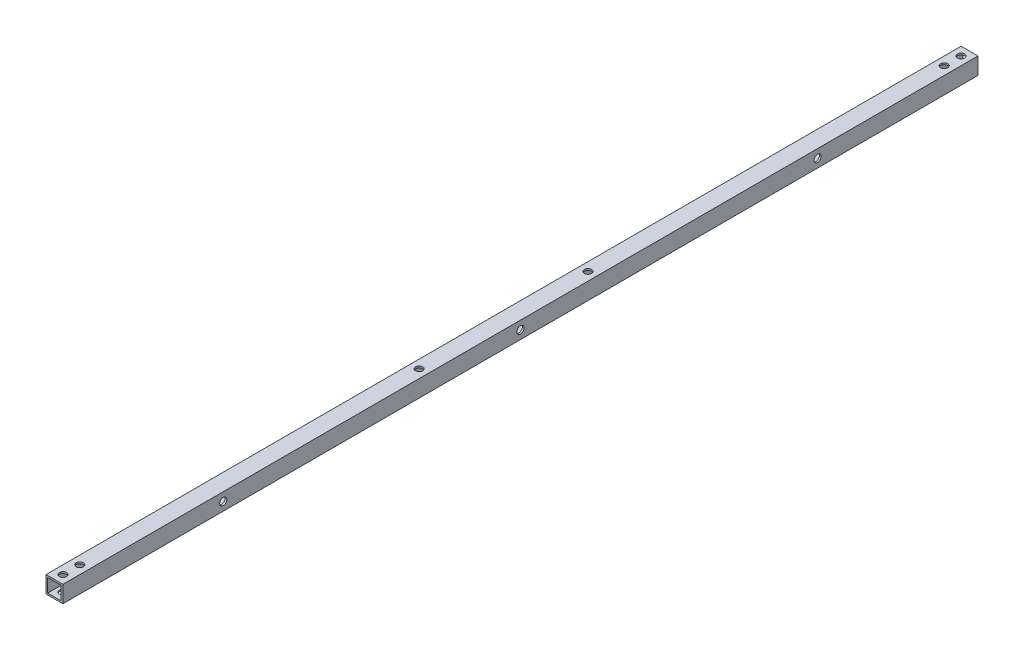
SolidWorks part; units mm, degrees
ref_plane "Front Plane" through (0, 0, 0) normal (0, 0, 1) x (1, 0, 0)
ref_plane "Top Plane" through (0, 0, 0) normal (0, 1, 0) x (1, 0, 0)
ref_plane "Right Plane" through (0, 0, 0) normal (1, 0, 0) x (0, 0, -1)
sketch "Sketch1" plane through (0, 0, 0) normal (0, 0, 1) x (1, 0, 0)
  line L1 (0, 0) -> (10, 0)
  line L2 (0, 0) -> (0, 10)
  line L3 (0, 10) -> (10, 10)
  line L4 (10, 0) -> (10, 10)
  line L5 (1, 9) -> (9, 9)
  line L6 (1, 9) -> (1, 1)
  line L7 (1, 1) -> (9, 1)
  line L8 (9, 9) -> (9, 1)
  dimension "D1" = 10
  dimension "D2" = 10
  dimension "D3" = 8
  dimension "D4" = 8
  dimension "D5" = 1
  dimension "D6" = 1
extrude "Boss-Extrude1" add sketch "Sketch1" along normal blind 542
sketch "Sketch2" plane through (0, 10, 0) normal (0, 1, 0) x (1, 0, 0)
  line L0 (10, 0) -> (0, 0) construction
  line L1 (10, -542) -> (10, 0) construction
  line L2 (0, -542) -> (0, 0) construction
  line L4 (10, -542) -> (0, -542) construction
  circle A0 centre (5, -5) radius 2.125
  circle A1 centre (5, -15) radius 2.125
  circle A2 centre (5, -527) radius 2.125
  circle A3 centre (5, -537) radius 2.125
  dimension "D1" = 4.25
  dimension "D2" = 4.25
  dimension "D7" = 4.25
  dimension "D8" = 4.25
  dimension "D9" = 5
  dimension "D10" = 5
  dimension "D11" = 15
  dimension "D12" = 5
  dimension "D3" = 5
  dimension "D4" = 15
  dimension "D5" = 5
  dimension "D6" = 5
extrude "Cut-Extrude1" cut sketch "Sketch2" against normal blind 116
sketch "Sketch3" plane through (0, 0, 0) normal (0, -1, 0) x (1, 0, 0)
  line L0 (10, 542) -> (10, 0) construction
  line L3 (0, 271) -> (10, 271) construction
  line L4 (0, 542) -> (0, 0) construction
  line L5 (0, 542) -> (10, 542) construction
  circle A0 centre (5, 326) radius 2.1
  circle A1 centre (5, 226) radius 2.125
  dimension "D1" = 4.25
  dimension "D2" = 5
  dimension "D3" = 216
  dimension "D4" = 100
  dimension "4.25" = 4.2
  dimension "D5" = 5
extrude "Cut-Extrude2" cut sketch "Sketch3" against normal blind 10
sketch "Sketch5" plane through (10, 0, 0) normal (1, 0, 0) x (0, 0, -1)
  line L1 (-542, 0) -> (-542, 10) construction
  line L2 (-542, 0) -> (0, 0) construction
  circle A0 centre (-447, 5) radius 2.125
  circle A1 centre (-95, 5) radius 2.125
  circle A2 centre (-271, 5) radius 2.125
  dimension "D1" = 4.25
  dimension "D2" = 4.25
  dimension "D3" = 4.25
  dimension "D4" = 176
  dimension "D5" = 95
  dimension "D6" = 271
  dimension "D7" = 5
extrude "Cut-Extrude3" cut sketch "Sketch5" against normal blind 10
